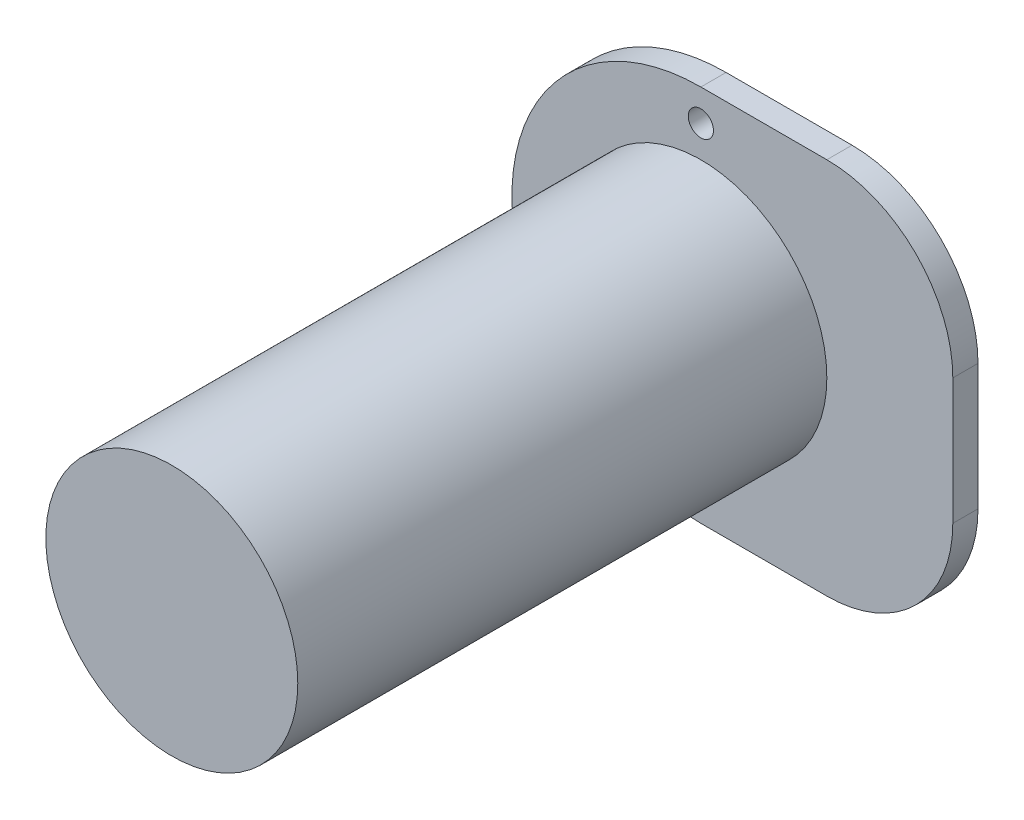
SolidWorks part; units mm, degrees
ref_plane "Front Plane" through (0, 0, 0) normal (0, 0, 1) x (1, 0, 0)
ref_plane "Top Plane" through (0, 0, 0) normal (0, 1, 0) x (1, 0, 0)
ref_plane "Right Plane" through (0, 0, 0) normal (1, 0, 0) x (0, 0, -1)
sketch "Sketch1" plane through (0, 0, 0) normal (0, 0, 1) x (1, 0, 0)
  circle A0 centre (0, 0) radius 50
  dimension "D1" = 100
extrude "Boss-Extrude1" add sketch "Sketch1" along normal blind 210
sketch "Sketch2" plane through (0, 0, 0) normal (0, 0, -1) x (-1, 0, 0)
  line L1 (0, -75) -> (-100, -75)
  line L3 (0, 75) -> (-100, 75)
  line L4 (-100, -75) -> (-100, 75)
  arc A0 (0, -75) -> (0, 75) centre (0, 0) ccw
  point P7 (0, 74.5706)
  dimension "D1" = 150
  dimension "D2" = 100
extrude "Boss-Extrude2" add sketch "Sketch2" along normal blind 10
sketch "Sketch3" plane through (0, 0, -10) normal (0, 0, -1) x (-1, 0, 0)
  circle A0 centre (0, 0) radius 62.5 construction
  circle A1 centre (0, 62.5) radius 5
  circle A2 centre (0, -62.5) radius 5
  circle A3 centre (62.5, 0) radius 5
  dimension "D1" = 10
  dimension "D2" = 125
extrude "Cut-Extrude1" cut sketch "Sketch3" against normal up to next
fillet "Fillet1" radius 50 2 edges at (100, -75, -5) (100, 75, -5)
